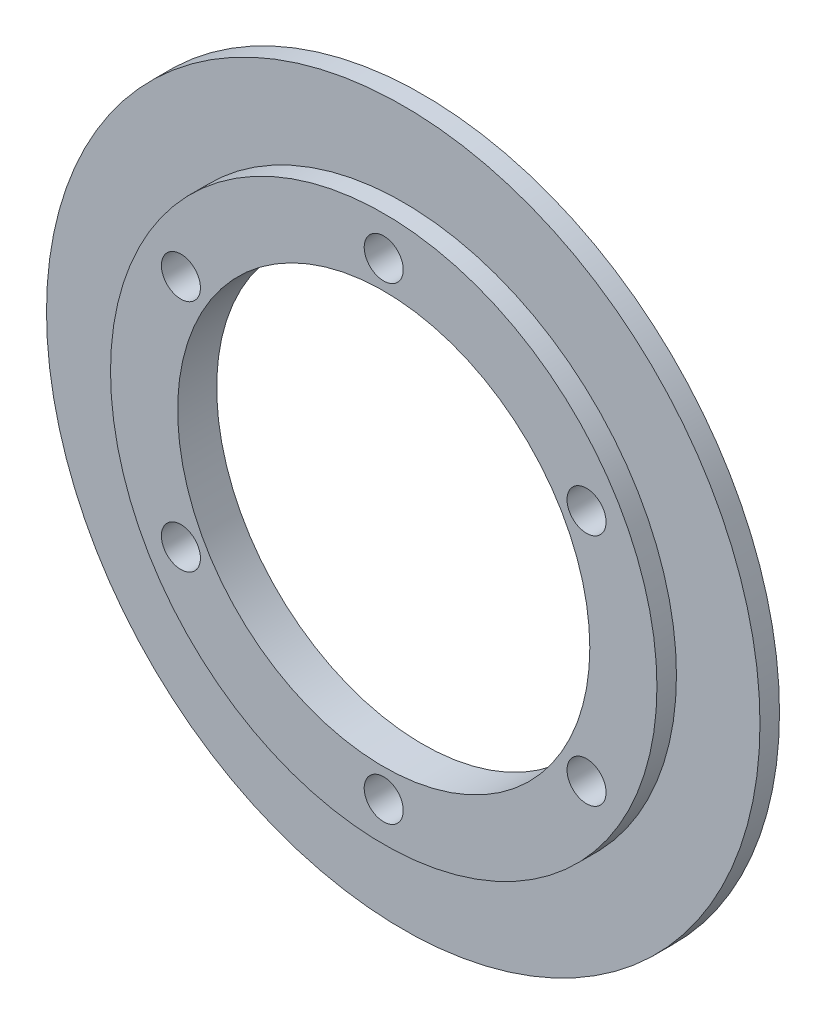
SolidWorks part; units mm, degrees
material "Cast Carbon Steel"
ref_plane "Front Plane" through (0, 0, 0) normal (0, 0, 1) x (1, 0, 0)
ref_plane "Top Plane" through (0, 0, 0) normal (0, 1, 0) x (1, 0, 0)
ref_plane "Right Plane" through (0, 0, 0) normal (1, 0, 0) x (0, 0, -1)
sketch "Sketch1" plane through (0, 0, 0) normal (0, 0, 1) x (1, 0, 0)
  circle A0 centre (0, 0) radius 457
  dimension "D2" = 914
extrude "Boss-Extrude1" add sketch "Sketch1" along normal blind 25
sketch "Sketch2" plane through (0, 0, 25) normal (0, 0, 1) x (1, 0, 0)
  circle A2 centre (0, 0) radius 350
  point P1 (0, 0)
  point P2 (0, 0)
  point P4 (-293.1426, -84.2442)
  dimension "D1" = 700
extrude "Boss-Extrude2" add sketch "Sketch2" along normal blind 25
sketch "Sketch3" plane through (0, 0, 50) normal (0, 0, 1) x (1, 0, 0)
  line L0 (0, 0) -> (0, 300) construction
  line L1 (0, 0) -> (0, 300) construction
  circle A0 centre (0, 300) radius 25
  circle A2 centre (259.8076, 150) radius 25
  circle A3 centre (259.8076, -150) radius 25
  circle A4 centre (0, -300) radius 25
  circle A5 centre (-259.8076, -150) radius 25
  circle A6 centre (-259.8076, 150) radius 25
  circle A7 centre (0, 0) radius 264
  dimension "D1" = 528
  dimension "D2" = 50
  dimension "D4" = 300
  dimension "D3" = 6
extrude "Cut-Extrude3" cut sketch "Sketch3" against normal through all and the other way through all contours A7 | A3 | A5 | A0 | A6 | A2 | A4
